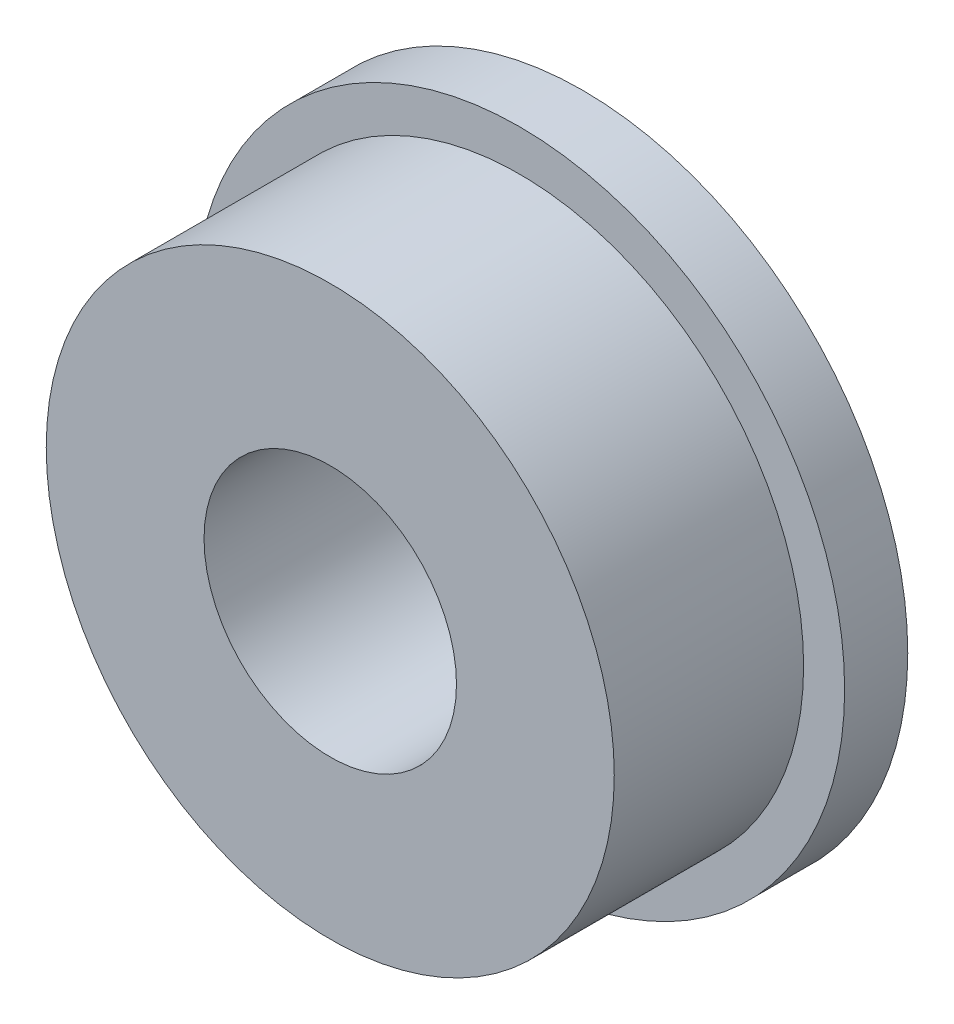
SolidWorks part; units mm, degrees
ref_plane "Front Plane" through (0, 0, 0) normal (0, 0, 1) x (1, 0, 0)
ref_plane "Top Plane" through (0, 0, 0) normal (0, 1, 0) x (1, 0, 0)
ref_plane "Right Plane" through (0, 0, 0) normal (1, 0, 0) x (0, 0, -1)
sketch "Sketch1" plane through (0, 0, 0) normal (0, 0, 1) x (1, 0, 0)
  circle A0 centre (0, 0) radius 2
  circle A1 centre (0, 0) radius 4.5
  dimension "D1" = 4
  dimension "D2" = 9
extrude "Boss-Extrude1" add sketch "Sketch1" along normal blind 4
sketch "Sketch2" plane through (0, 0, 0) normal (0, 0, -1) x (-1, 0, 0)
  circle A0 centre (0, 0) radius 5.15
  circle A1 centre (0, 0) radius 2
  circle A2 centre (0, 0) radius 2 construction
  dimension "D1" = 10.3
extrude "Boss-Extrude2" add sketch "Sketch2" against normal blind 1
